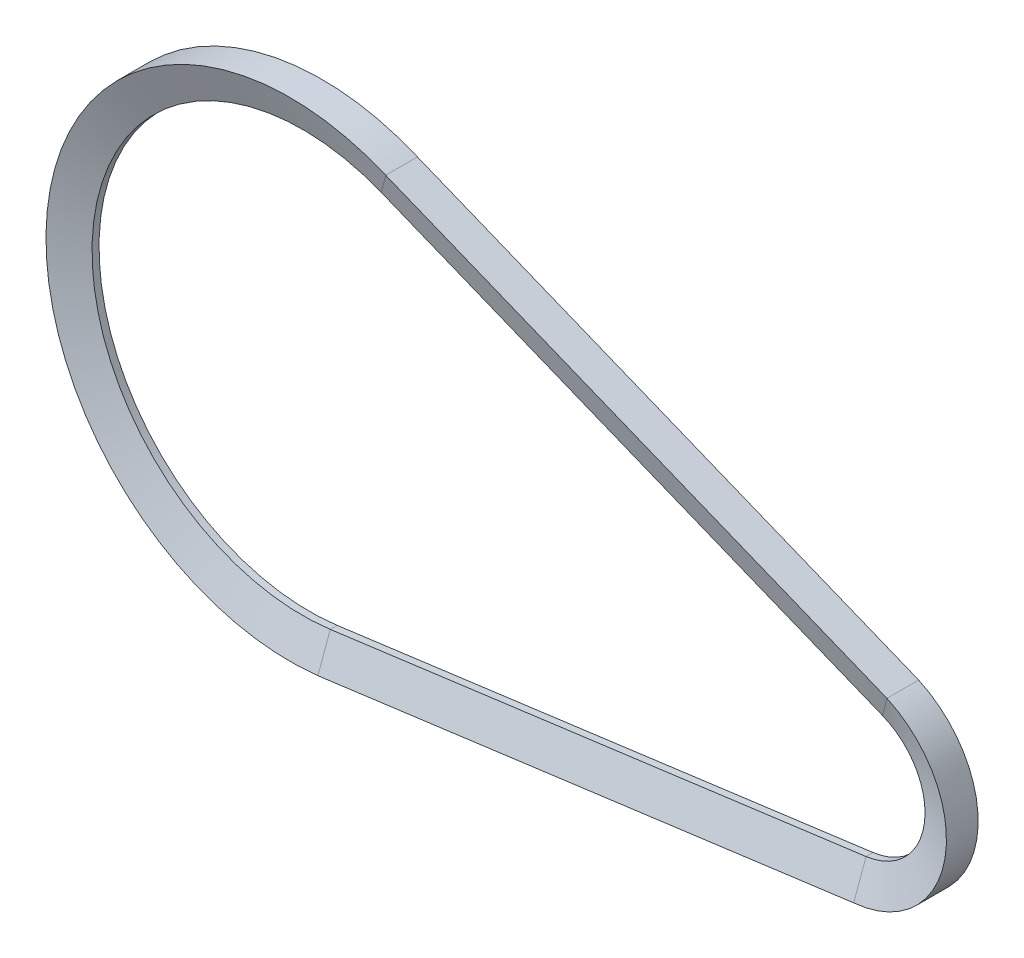
SolidWorks part; units mm, degrees
material "Silicon Rubber"
ref_plane "Front Plane" through (0, 0, 0) normal (0, 0, 1) x (1, 0, 0)
ref_plane "Top Plane" through (0, 0, 0) normal (0, 1, 0) x (1, 0, 0)
ref_plane "Right Plane" through (0, 0, 0) normal (1, 0, 0) x (0, 0, -1)
sketch "Sketch1" plane through (0, 0, 0) normal (0, 0, 1) x (1, 0, 0)
  line L0 (17.4127, 43.1167) -> (128.117, -1.5914)
  line L1 (6.1247, -46.0949) -> (124.4757, -30.3693)
  arc A0 (17.4127, 43.1167) -> (6.1247, -46.0949) centre (0, 0) ccw
  arc A1 (124.4757, -30.3693) -> (128.117, -1.5914) centre (122.5, -15.5) ccw
  dimension "D2" = 93
  dimension "D3" = 30
  dimension "D1" = 15.5
  dimension "D4" = 122.5
ref_plane "Plane1" through (6.1247, 0, 0) normal (-1, 0, 0) x (0, 0, 1)
sketch "Sketch4" plane through (6.1247, 0, 0) normal (-1, 0, 0) x (0, 0, 1)
  line L0 (0, -46.0949) -> (0, -5.896) construction
  line L1 (-0.7702, -46.0949) -> (0.7702, -46.0949)
  line L2 (-3.5, -53.5949) -> (3.5, -53.5949)
  line L3 (3.5, -53.5949) -> (0.7702, -46.0949)
  line L4 (-3.5, -53.5949) -> (-0.7702, -46.0949)
  line L5 (0, -46.0949) -> (0, -53.5949) construction
  dimension "D1" = 7
  dimension "D2" = 7.5
  dimension "D3" = 40
sweep "Sweep1" add profiles "Sketch4" path "Sketch1"
